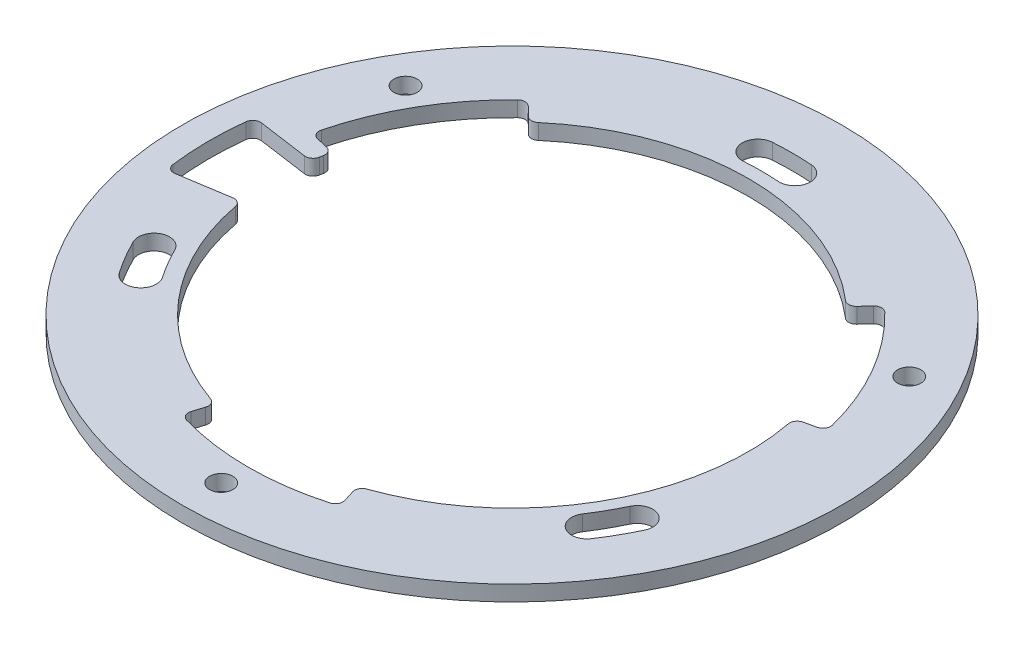
SolidWorks part; units mm, degrees
material "6061-T6 (SS)"
ref_plane "Front Plane" through (0, 0, 0) normal (0, 0, 1) x (1, 0, 0)
ref_plane "Top Plane" through (0, 0, 0) normal (0, 1, 0) x (1, 0, 0)
ref_plane "Right Plane" through (0, 0, 0) normal (1, 0, 0) x (0, 0, -1)
sketch "Sketch1" plane through (0, 0, 0) normal (0, 1, 0) x (1, 0, 0)
  line L0 (49.872, -261.8935) -> (473.872, -261.8935) construction
  line L9 (0, 42.5) -> (0, -42.5) construction
  line L10 (-42.5, 0) -> (42.5, 0) construction
  line L11 (0, 34.174) -> (-29.6727, -17.4567) construction
  line L12 (-32.476, 18.75) -> (0, -37.5) construction
  line L13 (0, -37.5) -> (32.476, 18.75) construction
  line L14 (32.476, 18.75) -> (-32.476, 18.75) construction
  line L15 (-32.476, 18.75) -> (16.238, -9.375) construction
  line L16 (-29.6727, -17.4567) -> (29.6727, -16.7173) construction
  line L17 (29.6727, -16.7173) -> (0, 34.174) construction
  line L18 (0, 34.174) -> (0, -17.087) construction
  line L19 (-29.6727, -17.4567) -> (14.8363, 8.7284) construction
  line L20 (0, -37.5) -> (0, 18.75) construction
  circle A22 centre (0, 0) radius 30.5
  circle A24 centre (0, 34.174) radius 1.5
  circle A25 centre (-29.6727, -17.4567) radius 1.5
  circle A26 centre (29.6727, -16.7173) radius 1.5
  circle A27 centre (0, 34.174) radius 2.675 construction
  circle A28 centre (-29.6727, -17.4567) radius 2.675 construction
  circle A29 centre (29.6727, -16.7173) radius 2.675 construction
  circle A30 centre (0, 0) radius 42.5
  circle A31 centre (-32.476, 18.75) radius 1.5
  circle A32 centre (0, -37.5) radius 1.5
  circle A33 centre (32.476, 18.75) radius 1.5
  circle A34 centre (0, 0) radius 30 construction
  point P19 (0, 0)
  point P22 (0, 0)
  point P65 (0, 0)
  point P69 (0, 0)
  point P70 (0, 0)
  dimension "D1" = 3
  dimension "D2" = 60
  dimension "D3" = 61
  dimension "D4" = 3
  dimension "D5" = 5.35
  dimension "D6" = 64.26
  dimension "D7" = 64.7
  dimension "D8" = 64.9
  dimension "D9" = 85
  dimension "D10" = 37.5
extrude "Boss-Extrude1" add sketch "Sketch1" along normal blind 2
sketch "Sketch2" plane through (0, 2, 0) normal (0, 1, 0) x (1, 0, 0)
  line L0 (0, 0) -> (0, 34.174) construction
  line L1 (0, 0) -> (-29.6727, -17.4567) construction
  line L2 (0, 0) -> (29.6727, -16.7173) construction
  line L3 (0, 0) -> (-2.3839, 34.0908) construction
  line L4 (0, 0) -> (2.3839, 34.0908) construction
  line L5 (0, 34.174) -> (0, 0) construction
  line L6 (0, 0) -> (-28.3827, -19.4841) construction
  line L7 (0, 0) -> (-30.8181, -15.3444) construction
  line L8 (-29.6727, -17.4567) -> (0, 0) construction
  line L9 (0, 0) -> (30.7666, -14.6067) construction
  line L10 (0, 0) -> (28.4343, -18.7464) construction
  line L11 (29.6727, -16.7173) -> (0, 0) construction
  circle A3 centre (29.6727, -16.7173) radius 1.5 construction
  circle A5 centre (-29.6727, -17.4567) radius 1.5 construction
  circle A7 centre (0, 34.174) radius 1.5 construction
  circle A11 centre (29.6727, -16.7173) radius 1.5
  circle A13 centre (-29.6727, -17.4567) radius 1.5
  circle A15 centre (0, 34.174) radius 1.5
  arc A16 (-2.3839, 34.0908) -> (2.3839, 34.0908) centre (0, 0) cw construction
  arc A17 (2.5234, 36.0859) -> (-2.5234, 36.0859) centre (0, 0) ccw
  arc A18 (2.2443, 32.0956) -> (-2.2443, 32.0956) centre (0, 0) ccw
  arc A19 (2.2443, 32.0956) -> (2.5234, 36.0859) centre (2.3839, 34.0908) ccw
  arc A20 (-2.5234, 36.0859) -> (-2.2443, 32.0956) centre (-2.3839, 34.0908) ccw
  arc A21 (-28.3827, -19.4841) -> (-30.8181, -15.3444) centre (0, 0) cw construction
  arc A22 (-32.6085, -16.2358) -> (-30.0316, -20.616) centre (0, 0) ccw
  arc A23 (-29.0278, -14.4529) -> (-26.7338, -18.3522) centre (0, 0) ccw
  arc A24 (-29.0278, -14.4529) -> (-32.6085, -16.2358) centre (-30.8181, -15.3444) ccw
  arc A25 (-30.0316, -20.616) -> (-26.7338, -18.3522) centre (-28.3827, -19.4841) ccw
  arc A26 (30.7666, -14.6067) -> (28.4343, -18.7464) centre (0, 0) cw construction
  arc A27 (30.104, -19.8472) -> (32.5733, -15.4644) centre (0, 0) ccw
  arc A28 (26.7645, -17.6455) -> (28.9598, -13.7489) centre (0, 0) ccw
  arc A29 (26.7645, -17.6455) -> (30.104, -19.8472) centre (28.4343, -18.7464) ccw
  arc A30 (32.5733, -15.4644) -> (28.9598, -13.7489) centre (30.7666, -14.6067) ccw
  point P27 (0, 34.174)
  point P40 (-29.6727, -17.4567)
  point P52 (29.6727, -16.7173)
  dimension "D1" = 2
  dimension "D3" = 2
  dimension "D5" = 2
  dimension "D2" = 4
  dimension "D4" = 4
  dimension "D6" = 4
extrude "Cut-Extrude1" cut sketch "Sketch2" against normal through all
sketch "Sketch3" plane through (0, 2, 0) normal (0, 1, 0) x (1, 0, 0)
  line L0 (0, -30.5) -> (-26.4138, 15.25) construction
  line L1 (-26.4138, 15.25) -> (26.4138, 15.25) construction
  line L2 (26.4138, 15.25) -> (0, -30.5) construction
  line L3 (0, 15.25) -> (0, -30.5) construction
  line L4 (13.2069, -7.625) -> (-26.4138, 15.25) construction
  line L5 (-29.777, 6.6014) -> (-33.1941, 7.3589)
  line L6 (-20.4926, 22.5899) -> (-22.9701, 25.0674)
  line L7 (20.6055, 22.487) -> (22.9701, 25.0674)
  line L8 (29.777, 6.6014) -> (33.1941, 7.3589)
  line L9 (-9.1715, -29.0884) -> (-10.224, -32.4264)
  line L10 (9.1715, -29.0884) -> (10.224, -32.4264)
  line L11 (26.4138, 15.25) -> (-13.2069, -7.625) construction
  circle A1 centre (0, 0) radius 30.5 construction
  arc A3 (-9.1715, -29.0884) -> (9.1715, -29.0884) centre (0, 0) ccw
  arc A4 (-10.224, -32.4264) -> (10.224, -32.4264) centre (0, 0) ccw
  arc A5 (29.777, 6.6014) -> (20.6055, 22.487) centre (0, 0) ccw
  arc A6 (33.1941, 7.3589) -> (22.9701, 25.0674) centre (0, 0) ccw
  arc A7 (-20.4926, 22.5899) -> (-29.777, 6.6014) centre (0, 0) ccw
  arc A8 (-22.9701, 25.0674) -> (-33.1941, 7.3589) centre (0, 0) ccw
  point P11 (0, 0)
  dimension "D1" = 68
  dimension "D2" = 17.5
  dimension "D3" = 15
  dimension "D4" = 17.5
  dimension "D5" = 17.5
  dimension "D6" = 17.5
  dimension "D7" = 17.5
extrude "Cut-Extrude2" cut sketch "Sketch3" against normal through all
sketch "Sketch4" plane through (0, 2, 0) normal (0, 1, 0) x (1, 0, 0)
  line L0 (0, 0) -> (-27.9489, -16.4426) construction
  line L1 (-27.9489, -16.4426) -> (-31.3965, -18.4709) construction
  line L2 (0, 0) -> (-38.9987, -0.319) construction
  line L3 (-30.2009, 4.2613) -> (-38.6175, 5.4488)
  line L4 (-30.1271, -4.7548) -> (-38.5232, -6.0799)
  line L5 (0, 0) -> (-30.2009, 4.2613) construction
  line L6 (0, 0) -> (-30.1271, -4.7548) construction
  arc A0 (-29.0278, -14.4529) -> (-32.6085, -16.2358) centre (-30.8181, -15.3444) ccw construction
  arc A1 (-32.6085, -16.2358) -> (-30.0316, -20.616) centre (0, 0) ccw construction
  arc A2 (-30.0316, -20.616) -> (-26.7338, -18.3522) centre (-28.3827, -19.4841) ccw construction
  arc A3 (-29.0278, -14.4529) -> (-26.7338, -18.3522) centre (0, 0) ccw construction
  arc A4 (-29.0278, -14.4529) -> (-32.6085, -16.2358) centre (-30.8181, -15.3444) ccw construction
  arc A5 (-32.6085, -16.2358) -> (-30.0316, -20.616) centre (0, 0) ccw construction
  arc A6 (-30.0316, -20.616) -> (-26.7338, -18.3522) centre (-28.3827, -19.4841) ccw construction
  arc A7 (-29.0278, -14.4529) -> (-26.7338, -18.3522) centre (0, 0) ccw construction
  arc A8 (-38.6175, 5.4488) -> (-38.5232, -6.0799) centre (0, 0) ccw
  arc A9 (-30.2009, 4.2613) -> (-30.1271, -4.7548) centre (0, 0) ccw
  point P12 (-29.6727, -17.4567)
  dimension "D4" = 78
  dimension "D1" = 30
  dimension "D2" = 8.5
  dimension "D3" = 8.5
extrude "Cut-Extrude3" cut sketch "Sketch4" against normal through all
fillet "Fillet1" radius 1 16 edges at (-9.1715, 1, 29.0884) (-10.224, 1, 32.4264) (10.224, 1, 32.4264) (9.1715, 1, 29.0884) (29.777, 1, -6.6014) (33.1941, 1, -7.3589) (22.9701, 1, -25.0674) (20.6055, 1, -22.487) (-20.4926, 1, -22.5899) (-22.9701, 1, -25.0674) (-33.1941, 1, -7.3589) (-29.777, 1, -6.6014) (-30.2009, 1, -4.2613) (-38.6175, 1, -5.4488) (-38.5232, 1, 6.0799) (-30.1271, 1, 4.7548)
